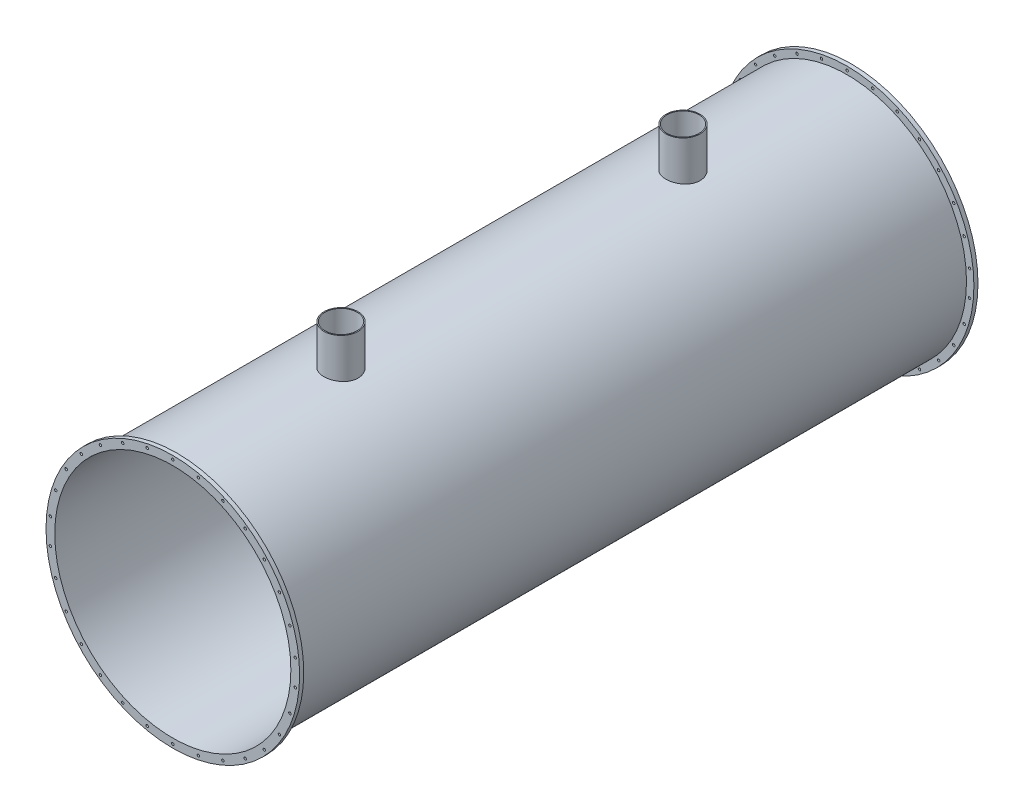
SolidWorks part; units mm, degrees
ref_plane "Front Plane" through (0, 0, 0) normal (0, 0, 1) x (1, 0, 0)
ref_plane "Top Plane" through (0, 0, 0) normal (0, 1, 0) x (1, 0, 0)
ref_plane "Right Plane" through (0, 0, 0) normal (1, 0, 0) x (0, 0, -1)
sketch "Sketch1" plane through (0, 0, 0) normal (0, 0, 1) x (1, 0, 0)
  circle A0 centre (0, 0) radius 2130.0235
  circle A1 centre (0, 0) radius 2105.58
  dimension "D1" = 4260.047
  dimension "D2" = 4211.16
extrude "Boss-Extrude1" add sketch "Sketch1" along normal blind 12100
ref_plane "Plane1" through (0, 2830.0235, 0) normal (0, 1, 0) x (1, 0, 0)
sketch "Sketch2" plane through (0, 2830.0235, 0) normal (0, 1, 0) x (1, 0, 0)
  line L0 (2130.0235, 0) -> (-2130.0235, 0) construction
  line L1 (-2130.0235, -12100) -> (2130.0235, -12100) construction
  circle A0 centre (0, -3000) radius 304.8
  circle A1 centre (0, -9100) radius 304.8
  dimension "D2" = 609.6
  dimension "D3" = 3000
  dimension "D4" = 3000
extrude "Boss-Extrude2" add sketch "Sketch2" against normal up to surface up to face at (2130.0235, 0, 12100)
sketch "Sketch3" plane through (0, 2830.0235, 0) normal (0, 1, 0) x (1, 0, 0)
  circle A0 centre (0, -9100) radius 287
  circle A1 centre (0, -3000) radius 287
  dimension "D1" = 574
extrude "Cut-Extrude1" cut sketch "Sketch3" against normal blind 1000
sketch "Sketch4" plane through (0, 0, 12100) normal (0, 0, 1) x (1, 0, 0)
  circle A0 centre (0, 0) radius 2262.0235
  circle A1 centre (0, 0) radius 2130.0235 construction
  circle A2 centre (0, 0) radius 2130.0235
  dimension "D1" = 4524.047
extrude "Boss-Extrude3" add sketch "Sketch4" against normal blind 73
sketch "Sketch5" plane through (0, 0, 12100) normal (0, 0, 1) x (1, 0, 0)
  circle A0 centre (0, 0) radius 2196.035 construction
  circle A1 centre (0, 2196.035) radius 22
  circle A2 centre (456.5813, 2148.0464) radius 22
  circle A3 centre (893.2079, 2006.1778) radius 22
  circle A4 centre (1290.797, 1776.6296) radius 22
  circle A5 centre (1631.972, 1469.4342) radius 22
  circle A6 centre (1901.8221, 1098.0175) radius 22
  circle A7 centre (2088.5534, 678.6121) radius 22
  circle A8 centre (2184.0049, 229.5482) radius 22
  circle A9 centre (2184.0049, -229.5482) radius 22
  circle A10 centre (2088.5534, -678.6121) radius 22
  circle A11 centre (1901.8221, -1098.0175) radius 22
  circle A12 centre (1631.972, -1469.4342) radius 22
  circle A13 centre (1290.797, -1776.6296) radius 22
  circle A14 centre (893.2079, -2006.1778) radius 22
  circle A15 centre (456.5813, -2148.0464) radius 22
  circle A16 centre (0, -2196.035) radius 22
  circle A17 centre (-456.5813, -2148.0464) radius 22
  circle A18 centre (-893.2079, -2006.1778) radius 22
  circle A19 centre (-1290.797, -1776.6296) radius 22
  circle A20 centre (-1631.972, -1469.4342) radius 22
  circle A21 centre (-1901.8221, -1098.0175) radius 22
  circle A22 centre (-2088.5534, -678.6121) radius 22
  circle A23 centre (-2184.0049, -229.5482) radius 22
  circle A24 centre (-2184.0049, 229.5482) radius 22
  circle A25 centre (-2088.5534, 678.6121) radius 22
  circle A26 centre (-1901.8221, 1098.0175) radius 22
  circle A27 centre (-1631.972, 1469.4342) radius 22
  circle A28 centre (-1290.797, 1776.6296) radius 22
  circle A29 centre (-893.2079, 2006.1778) radius 22
  circle A30 centre (-456.5813, 2148.0464) radius 22
  point P66 (0, 0)
  dimension "D1" = 44
  dimension "D2" = 4392.07
  dimension "D3" = 30
extrude "Cut-Extrude3" cut sketch "Sketch5" against normal up to next (73 mm away)
sketch "Sketch7" plane through (0, 0, 0) normal (0, 0, -1) x (-1, 0, 0)
  circle A1 centre (0, 0) radius 2130.0235
  circle A2 centre (0, 0) radius 2130.0235
  circle A3 centre (0, 0) radius 2262.0235
  circle A4 centre (0, 0) radius 2262.0235
  dimension "D1" = 0
  dimension "D2" = 0
extrude "Boss-Extrude4" add sketch "Sketch7" against normal blind 73
sketch "Sketch8" plane through (0, 0, 0) normal (0, 0, -1) x (-1, 0, 0)
  circle A1 centre (-1631.972, 1469.4342) radius 22
  circle A2 centre (-1631.972, 1469.4342) radius 22
  circle A3 centre (-1290.797, 1776.6296) radius 22
  circle A4 centre (-1290.797, 1776.6296) radius 22
  circle A5 centre (-893.2079, 2006.1778) radius 22
  circle A6 centre (-893.2079, 2006.1778) radius 22
  circle A7 centre (-456.5813, 2148.0464) radius 22
  circle A8 centre (-456.5813, 2148.0464) radius 22
  circle A9 centre (0, 2196.035) radius 22
  circle A10 centre (0, 2196.035) radius 22
  circle A11 centre (-1290.797, -1776.6296) radius 22
  circle A12 centre (-1290.797, -1776.6296) radius 22
  circle A13 centre (-1631.972, -1469.4342) radius 22
  circle A14 centre (-1631.972, -1469.4342) radius 22
  circle A15 centre (-1901.8221, -1098.0175) radius 22
  circle A16 centre (-1901.8221, -1098.0175) radius 22
  circle A17 centre (-2088.5534, -678.6121) radius 22
  circle A18 centre (-2088.5534, -678.6121) radius 22
  circle A19 centre (-2184.0049, -229.5482) radius 22
  circle A20 centre (-2184.0049, -229.5482) radius 22
  circle A21 centre (-2184.0049, 229.5482) radius 22
  circle A22 centre (-2184.0049, 229.5482) radius 22
  circle A23 centre (-2088.5534, 678.6121) radius 22
  circle A24 centre (-2088.5534, 678.6121) radius 22
  circle A25 centre (-1901.8221, 1098.0175) radius 22
  circle A26 centre (-1901.8221, 1098.0175) radius 22
  circle A27 centre (1901.8221, -1098.0175) radius 22
  circle A28 centre (1901.8221, -1098.0175) radius 22
  circle A29 centre (1631.972, -1469.4342) radius 22
  circle A30 centre (1631.972, -1469.4342) radius 22
  circle A31 centre (1290.797, -1776.6296) radius 22
  circle A32 centre (1290.797, -1776.6296) radius 22
  circle A33 centre (893.2079, -2006.1778) radius 22
  circle A34 centre (893.2079, -2006.1778) radius 22
  circle A35 centre (456.5813, -2148.0464) radius 22
  circle A36 centre (456.5813, -2148.0464) radius 22
  circle A37 centre (0, -2196.035) radius 22
  circle A38 centre (0, -2196.035) radius 22
  circle A39 centre (-456.5813, -2148.0464) radius 22
  circle A40 centre (-456.5813, -2148.0464) radius 22
  circle A41 centre (-893.2079, -2006.1778) radius 22
  circle A42 centre (-893.2079, -2006.1778) radius 22
  circle A43 centre (893.2079, 2006.1778) radius 22
  circle A44 centre (893.2079, 2006.1778) radius 22
  circle A45 centre (1290.797, 1776.6296) radius 22
  circle A46 centre (1290.797, 1776.6296) radius 22
  circle A47 centre (1631.972, 1469.4342) radius 22
  circle A48 centre (1631.972, 1469.4342) radius 22
  circle A49 centre (1901.8221, 1098.0175) radius 22
  circle A50 centre (1901.8221, 1098.0175) radius 22
  circle A51 centre (2088.5534, 678.6121) radius 22
  circle A52 centre (2088.5534, 678.6121) radius 22
  circle A53 centre (2184.0049, 229.5482) radius 22
  circle A54 centre (2184.0049, 229.5482) radius 22
  circle A55 centre (2184.0049, -229.5482) radius 22
  circle A56 centre (2184.0049, -229.5482) radius 22
  circle A57 centre (2088.5534, -678.6121) radius 22
  circle A58 centre (2088.5534, -678.6121) radius 22
  circle A59 centre (456.5813, 2148.0464) radius 22
  circle A60 centre (456.5813, 2148.0464) radius 22
  dimension "D1" = 0
  dimension "D2" = 0
  dimension "D3" = 0
  dimension "D4" = 0
  dimension "D5" = 0
  dimension "D6" = 0
  dimension "D7" = 0
  dimension "D8" = 0
  dimension "D9" = 0
  dimension "D10" = 0
  dimension "D11" = 0
  dimension "D12" = 0
  dimension "D13" = 0
  dimension "D14" = 0
  dimension "D15" = 0
  dimension "D16" = 0
  dimension "D17" = 0
  dimension "D18" = 0
  dimension "D19" = 0
  dimension "D20" = 0
  dimension "D21" = 0
  dimension "D22" = 0
  dimension "D23" = 0
  dimension "D24" = 0
  dimension "D25" = 0
  dimension "D26" = 0
  dimension "D27" = 0
  dimension "D28" = 0
  dimension "D29" = 0
  dimension "D30" = 0
extrude "Cut-Extrude4" cut sketch "Sketch8" against normal up to next (73 mm away)
